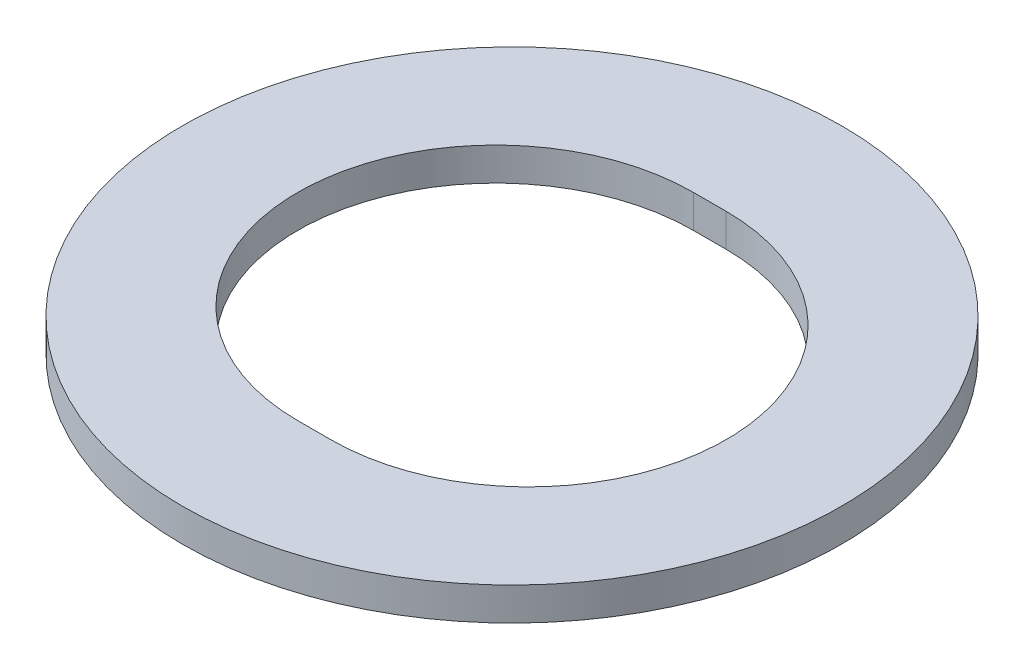
SolidWorks part; units mm, degrees
ref_plane "Front Plane" through (0, 0, 0) normal (0, 0, 1) x (1, 0, 0)
ref_plane "Top Plane" through (0, 0, 0) normal (0, 1, 0) x (1, 0, 0)
ref_plane "Right Plane" through (0, 0, 0) normal (1, 0, 0) x (0, 0, -1)
sketch "Sketch1" plane through (0, 0, 0) normal (0, 1, 0) x (1, 0, 0)
  line L0 (-0.5, 0) -> (0.5, 0) construction
  line L1 (-0.5, 6) -> (0.5, 6)
  line L2 (-0.5, -6) -> (0.5, -6)
  circle A0 centre (0, 0) radius 10
  arc A1 (-0.5, 6) -> (-0.5, -6) centre (-0.5, 0) ccw
  arc A2 (0.5, -6) -> (0.5, 6) centre (0.5, 0) ccw
  point P3 (0, 0)
  point P10 (0, 0)
  dimension "D1" = 12
  dimension "D2" = 20
  dimension "D3" = 1
extrude "Boss-Extrude1" add sketch "Sketch1" along normal blind 1
